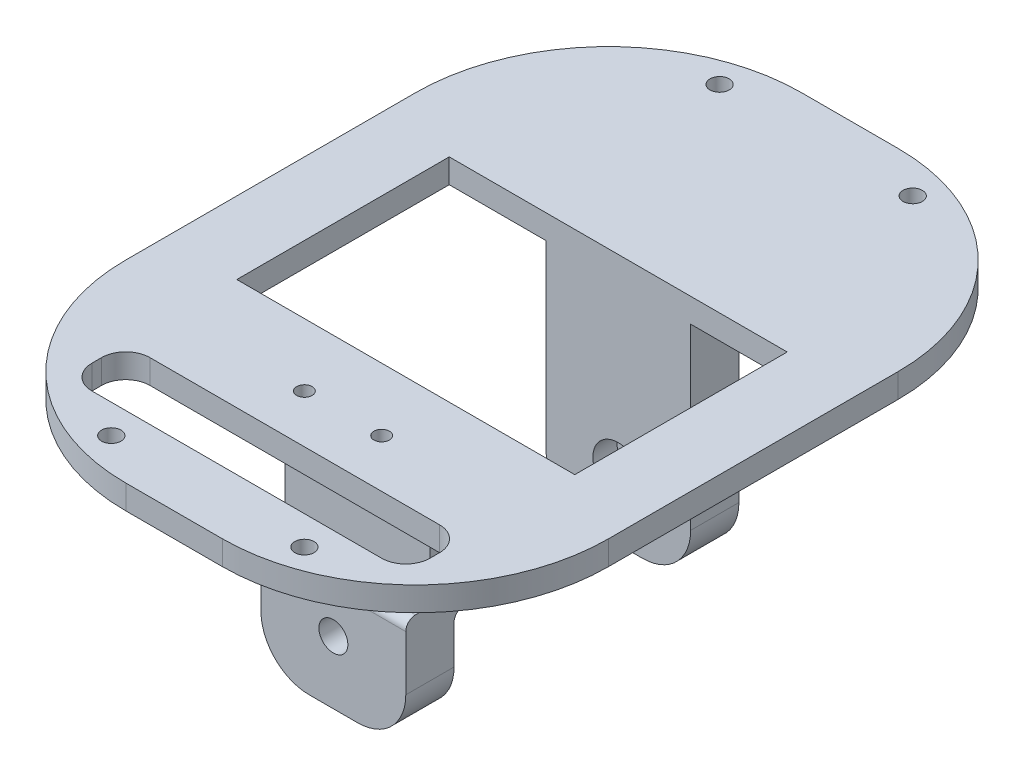
SolidWorks part; units mm, degrees
ref_plane "Front Plane" through (0, 0, 0) normal (0, 0, 1) x (1, 0, 0)
ref_plane "Top Plane" through (0, 0, 0) normal (0, 1, 0) x (1, 0, 0)
ref_plane "Right Plane" through (0, 0, 0) normal (1, 0, 0) x (0, 0, -1)
sketch "Sketch1" plane through (0, 0, 0) normal (0, 1, 0) x (1, 0, 0)
  line L1 (50, -45) -> (-50, -45)
  line L2 (50, -45) -> (50, 45)
  line L3 (50, 45) -> (-50, 45)
  line L4 (-50, -45) -> (-50, 45)
  line L5 (50, -45) -> (-50, 45) construction
  line L6 (50, 45) -> (-50, -45) construction
  point P0 (0, 0)
  dimension "D1" = 100
  dimension "D2" = 90
extrude "Boss-Extrude1" add sketch "Sketch1" along normal blind 5
sketch "Sketch2" plane through (0, 5, 0) normal (0, 1, 0) x (1, 0, 0)
  line L0 (0, 45) -> (0, -45) construction
  line L1 (50, 45) -> (-50, 45) construction
  line L2 (-50, -45) -> (50, -45) construction
  line L3 (-50, 0) -> (50, 0) construction
  line L4 (-50, 45) -> (-50, -45) construction
  line L5 (50, -45) -> (50, 45) construction
  line L7 (35, 22) -> (-35, 22)
  line L8 (35, 22) -> (35, -22)
  line L9 (35, -22) -> (-35, -22)
  line L10 (-35, 22) -> (-35, -22)
  line L11 (35, 22) -> (-35, -22) construction
  line L12 (35, -22) -> (-35, 22) construction
  point P12 (0, 0)
  dimension "D1" = 44
  dimension "D2" = 70
extrude "Cut-Extrude1" cut sketch "Sketch2" against normal through all
sketch "Sketch3" plane through (0, 5, 0) normal (0, 1, 0) x (1, 0, 0)
  line L0 (0, 45) -> (0, -45) construction
  line L1 (50, 45) -> (-50, 45) construction
  line L2 (-50, -45) -> (50, -45) construction
  line L3 (-50, 0) -> (50, 0) construction
  line L4 (-50, 45) -> (-50, -45) construction
  line L5 (50, -45) -> (50, 45) construction
  circle A0 centre (-8, -35) radius 1.6
  circle A1 centre (8, -35) radius 1.6
  dimension "D1" = 3.2
  dimension "D2" = 10
  dimension "D3" = 8
extrude "Cut-Extrude2" cut sketch "Sketch3" against normal through all
sketch "Sketch4" plane through (0, 5, 0) normal (0, 1, 0) x (1, 0, 0)
  line L0 (50, -45) -> (50, 45) construction
  line L1 (-50, -45) -> (50, -45)
  line L2 (-50, -45) -> (-50, -70)
  line L3 (-50, -70) -> (50, -70)
  line L4 (50, -45) -> (50, -70)
  line L6 (-50, 45) -> (50, 45)
  line L7 (-50, 45) -> (-50, 70)
  line L8 (-50, 70) -> (50, 70)
  line L9 (50, 45) -> (50, 70)
  dimension "D1" = 25
  dimension "D2" = 25
extrude "Boss-Extrude2" add sketch "Sketch4" against normal blind 5
sketch "Sketch6" plane through (0, 5, 0) normal (0, 1, 0) x (1, 0, 0)
  line L1 (35, -57) -> (-35, -57)
  line L2 (35, -57) -> (35, -45)
  line L3 (35, -45) -> (-35, -45)
  line L4 (-35, -57) -> (-35, -45)
  line L5 (35, -57) -> (-35, -45) construction
  line L6 (35, -45) -> (-35, -57) construction
  line L7 (-50, 70) -> (-50, -70) construction
  line L8 (50, -70) -> (50, 70) construction
  point P0 (0, -51)
  dimension "D1" = 12
  dimension "D3" = 15
  dimension "D4" = 15
extrude "Cut-Extrude4" cut sketch "Sketch6" against normal blind 17
sketch "Sketch8" plane through (0, 0, 0) normal (0, -1, 0) x (1, 0, 0)
  line L0 (0, 70) -> (0, -45) construction
  line L1 (-50, 70) -> (50, 70) construction
  line L5 (-35, 0) -> (35, 0) construction
  line L6 (15, 22) -> (-15, 22)
  line L7 (15, 22) -> (15, 32)
  line L8 (15, 32) -> (-15, 32)
  line L9 (-15, 22) -> (-15, 32)
  line L10 (15, 22) -> (-15, 32) construction
  line L11 (15, 32) -> (-15, 22) construction
  line L12 (-35, -22) -> (-35, 22) construction
  line L13 (35, 22) -> (35, -22) construction
  line L14 (15, -32) -> (-15, -22) construction
  line L15 (15, -22) -> (-15, -32) construction
  line L16 (-15, -22) -> (-15, -32)
  line L17 (15, -32) -> (-15, -32)
  line L18 (15, -22) -> (15, -32)
  line L19 (15, -22) -> (-15, -22)
  line L20 (-35, 22) -> (35, 22) construction
  point P13 (0, 27)
  point P28 (0, -27)
  dimension "D1" = 10
  dimension "D2" = 30
  dimension "D3" = 0
  dimension "D4" = 0
extrude "Boss-Extrude4" add sketch "Sketch8" along normal blind 47
sketch "Sketch11" plane through (0, 0, 22) normal (0, 0, -1) x (-1, 0, 0)
  circle A0 centre (0, -34) radius 5.25
  dimension "D1" = 10.5
  dimension "D2" = 34
extrude "Cut-Extrude5" cut sketch "Sketch11" against normal blind 5
sketch "Sketch12" plane through (0, 0, 27) normal (0, 0, -1) x (-1, 0, 0)
  circle A0 centre (0, -34) radius 3
  dimension "D1" = 6
extrude "Cut-Extrude6" cut sketch "Sketch12" against normal blind 5
fillet "Fillet1" radius 10 2 edges at (-15, -47, 27) (15, -47, 27)
sketch "Sketch13" plane through (0, 0, -22) normal (0, 0, 1) x (1, 0, 0)
  line L0 (35, 0) -> (15, 0) construction
  circle A0 centre (0, -34) radius 5.25
  dimension "D1" = 10.5
  dimension "D2" = 34
extrude "Cut-Extrude7" cut sketch "Sketch13" against normal blind 5
sketch "Sketch14" plane through (0, 0, -27) normal (0, 0, 1) x (1, 0, 0)
  circle A0 centre (0, -34) radius 3
  dimension "D1" = 6
extrude "Cut-Extrude8" cut sketch "Sketch14" against normal blind 5
fillet "Fillet2" radius 10 2 edges at (15, -47, -27) (-15, -47, -27)
sketch "Sketch15" plane through (0, 5, 0) normal (0, 1, 0) x (1, 0, 0)
  line L0 (0, 45) -> (0, -70) construction
  line L2 (-50, -70) -> (50, -70) construction
  line L3 (-50, 0) -> (50, 0) construction
  line L4 (-50, 70) -> (-50, -70) construction
  line L5 (50, -70) -> (50, 70) construction
  circle A0 centre (-20, -63) radius 2
  circle A2 centre (-20, 63) radius 2
  circle A3 centre (20, -63) radius 2
  circle A4 centre (20, 63) radius 2
  dimension "D1" = 4
  dimension "D2" = 20
  dimension "D3" = 7
extrude "Cut-Extrude9" cut sketch "Sketch15" against normal through all
fillet "Fillet3" radius 40 2 edges at (50, 2.5, 70) (-50, 2.5, 70)
fillet "Fillet4" radius 40 2 edges at (-50, 2.5, -70) (50, 2.5, -70)
fillet "Fillet5" radius 5 4 edges at (-35, 2.5, 57) (35, 2.5, 57) (35, 2.5, 45) (-35, 2.5, 45)
sketch "Sketch16" plane through (15, 0, 0) normal (1, 0, 0) x (0, 0, -1)
  line L0 (-32, -23.6524) -> (-37, -23.6524)
  line L1 (-32, -37) -> (-32, 0) construction
  line L2 (-37, -23.6524) -> (-37, -47)
  line L4 (-37, -47) -> (-27, -47)
  line L5 (-22, -47) -> (-32, -47) construction
  line L6 (-27, -47) -> (-27, -23.6524)
  line L7 (-27, -23.6524) -> (-32, -23.6524)
  line L8 (-22, -37) -> (-22, 0) construction
  dimension "D1" = 5
  dimension "D2" = 10
extrude "Boss-Extrude5" add sketch "Sketch16" against normal blind 30
sketch "Sketch17" plane through (0, 0, 22) normal (0, 0, -1) x (-1, 0, 0)
  circle A0 centre (0, -34) radius 5.25
extrude "Cut-Extrude10" cut sketch "Sketch17" against normal blind 10
sketch "Sketch18" plane through (0, 0, 22) normal (0, 0, -1) x (-1, 0, 0)
  circle A0 centre (0, -34) radius 3
  dimension "D1" = 6
extrude "Cut-Extrude12" cut sketch "Sketch18" against normal blind 21
sketch "Sketch19" plane through (0, 0, 22) normal (0, 0, -1) x (-1, 0, 0)
  line L2 (15, -47) -> (15, -37)
  line L3 (5, -47) -> (15, -47)
  line L4 (15, -47) -> (15, -37)
  line L5 (5, -47) -> (15, -47)
  line L6 (-15, -47) -> (-5, -47)
  line L7 (-15, -37) -> (-15, -47)
  line L8 (-5, -47) -> (5, -47)
  line L9 (15, -37) -> (15, 0)
  line L10 (15, 0) -> (35, 0)
  line L11 (35, 0) -> (35, 5)
  line L12 (35, 5) -> (-35, 5)
  line L13 (-35, 5) -> (-35, 0)
  line L14 (-35, 0) -> (-15, 0)
  line L15 (-15, 0) -> (-15, -37)
  line L16 (-5, -47) -> (5, -47)
  line L18 (15, 0) -> (35, 0)
  line L19 (35, 0) -> (35, 5)
  line L20 (35, 5) -> (-35, 5)
  line L21 (-35, 5) -> (-35, 0)
  line L22 (-35, 0) -> (-15, 0)
  line L24 (-15, -47) -> (-5, -47)
  line L25 (-15, -37) -> (-15, -47)
  arc A1 (5, -47) -> (15, -37) centre (5, -37) ccw
  arc A2 (5, -47) -> (15, -37) centre (5, -37) ccw
  arc A3 (-15, -37) -> (-5, -47) centre (-5, -37) ccw
  arc A4 (5, -47) -> (15, -37) centre (5, -37) ccw
  arc A5 (-15, -37) -> (-5, -47) centre (-5, -37) ccw
  arc A6 (5, -47) -> (15, -37) centre (5, -37) ccw
  arc A7 (-15, -37) -> (-5, -47) centre (-5, -37) ccw
  arc A8 (-15, -37) -> (-5, -47) centre (-5, -37) ccw
  arc M19 (5, -47) -> (15, -37) centre (5, -37) ccw
  arc M27 (-15, -37) -> (-5, -47) centre (-5, -37) ccw
  dimension "D1" = 0
  dimension "D2" = 0
  dimension "D3" = 0
extrude "Cut-Extrude13" cut sketch "Sketch19" against normal blind 21 contours L25 L24 M27 | L5 L4 M19
sketch "Sketch20" plane through (15, 0, 0) normal (1, 0, 0) x (0, 0, -1)
  line L1 (-22, -47) -> (-27, -47)
  line L2 (-22, -47) -> (-22, -27)
  line L3 (-22, -27) -> (-27, -27)
  line L4 (-27, -47) -> (-27, -27)
  dimension "D1" = 5
  dimension "D2" = 20
extrude "Cut-Extrude14" cut sketch "Sketch20" against normal through all
fillet "Fillet6" radius 2 2 edges at (0, -23.6524, 37) (0, -23.6524, 32)
fillet "Fillet7" radius 2 2 edges at (0, -27, 27) (0, -27, 22)
